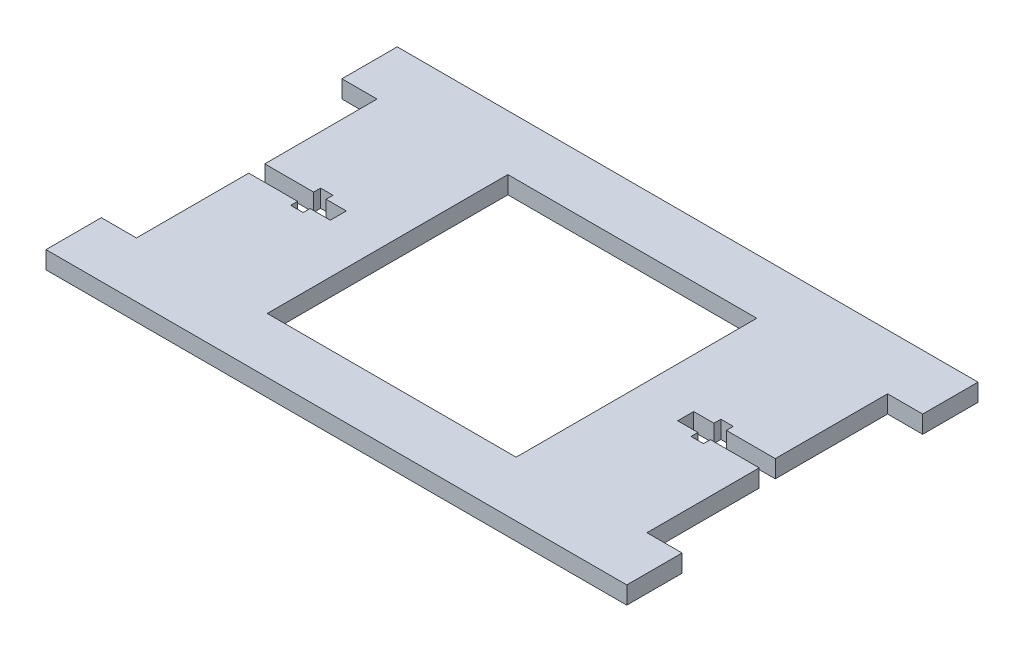
SolidWorks part; units mm, degrees
ref_plane "Front Plane" through (0, 0, 0) normal (0, 0, 1) x (1, 0, 0)
ref_plane "Top Plane" through (0, 0, 0) normal (0, 1, 0) x (1, 0, 0)
ref_plane "Right Plane" through (0, 0, 0) normal (1, 0, 0) x (0, 0, -1)
sketch "Sketch1" plane through (0, 0, 0) normal (0, 1, 0) x (1, 0, 0)
  line L0 (37.2275, -45.3753) -> (37.2275, -35.3753)
  line L1 (-67.7725, 18.1247) -> (37.2275, 18.1247)
  line L2 (30.8775, -35.3753) -> (30.8775, -15.0753)
  line L3 (-67.7725, -45.3753) -> (37.2275, -45.3753)
  line L4 (37.2275, 18.1247) -> (37.2275, 8.1247)
  line L5 (37.2275, 8.1247) -> (30.8775, 8.1247)
  line L6 (22.0375, -12.1753) -> (30.8775, -12.1753)
  line L7 (37.2275, -35.3753) -> (30.8775, -35.3753)
  line L8 (16.1275, -12.1753) -> (19.7875, -12.1753)
  line L9 (16.1275, -12.1753) -> (16.1275, -15.0753)
  line L10 (16.1275, -15.0753) -> (19.7875, -15.0753)
  line L11 (-67.7725, 8.1247) -> (-61.4225, 8.1247)
  line L12 (19.7875, -16.3253) -> (22.0375, -16.3253)
  line L13 (19.7875, -16.3253) -> (19.7875, -15.0753)
  line L14 (19.7875, -10.9253) -> (22.0375, -10.9253)
  line L15 (22.0375, -16.3253) -> (22.0375, -15.0753)
  line L16 (22.0375, -15.0753) -> (30.8775, -15.0753)
  line L17 (19.7875, -12.1753) -> (19.7875, -10.9253)
  line L18 (22.0375, -12.1753) -> (22.0375, -10.9253)
  line L19 (30.8775, -12.1753) -> (30.8775, 8.1247)
  line L21 (-52.5825, -12.1753) -> (-61.4225, -12.1753)
  line L22 (-52.5825, -12.1753) -> (-52.5825, -10.9253)
  line L23 (-50.3325, -12.1753) -> (-50.3325, -10.9253)
  line L24 (-52.5825, -15.0753) -> (-61.4225, -15.0753)
  line L25 (-52.5825, -16.3253) -> (-52.5825, -15.0753)
  line L26 (-50.3325, -10.9253) -> (-52.5825, -10.9253)
  line L27 (-50.3325, -16.3253) -> (-50.3325, -15.0753)
  line L28 (-50.3325, -16.3253) -> (-52.5825, -16.3253)
  line L29 (-46.6725, -15.0753) -> (-50.3325, -15.0753)
  line L30 (-46.6725, -12.1753) -> (-46.6725, -15.0753)
  line L31 (-46.6725, -12.1753) -> (-50.3325, -12.1753)
  line L32 (-67.7725, -35.3753) -> (-61.4225, -35.3753)
  line L33 (-61.4225, -35.3753) -> (-61.4225, -15.0753)
  line L34 (-67.7725, -45.3753) -> (-67.7725, -35.3753)
  line L35 (-61.4225, -12.1753) -> (-61.4225, 8.1247)
  line L36 (-67.7725, 18.1247) -> (-67.7725, 8.1247)
  line L37 (-37.7725, 8.1247) -> (7.2275, 8.1247)
  line L38 (-37.7725, 8.1247) -> (-37.7725, -35.3753)
  line L39 (-37.7725, -35.3753) -> (7.2275, -35.3753)
  line L40 (7.2275, 8.1247) -> (7.2275, -35.3753)
  point P40 (-15.2725, -35.3753)
  dimension "D1" = 105
  dimension "D2" = 63.5
  dimension "D3" = 10
  dimension "D4" = 10
  dimension "D5" = 6.35
  dimension "D6" = 20.3
  dimension "D7" = 20.3
  dimension "D8" = 2.9
  dimension "D9" = 14.75
  dimension "D10" = 2.25
  dimension "D11" = 1.25
  dimension "D12" = 8.84
  dimension "D13" = 1.25
  dimension "D14" = 43.5
  dimension "D15" = 45
  dimension "D16" = 10
  dimension "D17" = 105
  dimension "D18" = 52.5
extrude "Extrude1" add sketch "Sketch1" along normal blind 3.175
